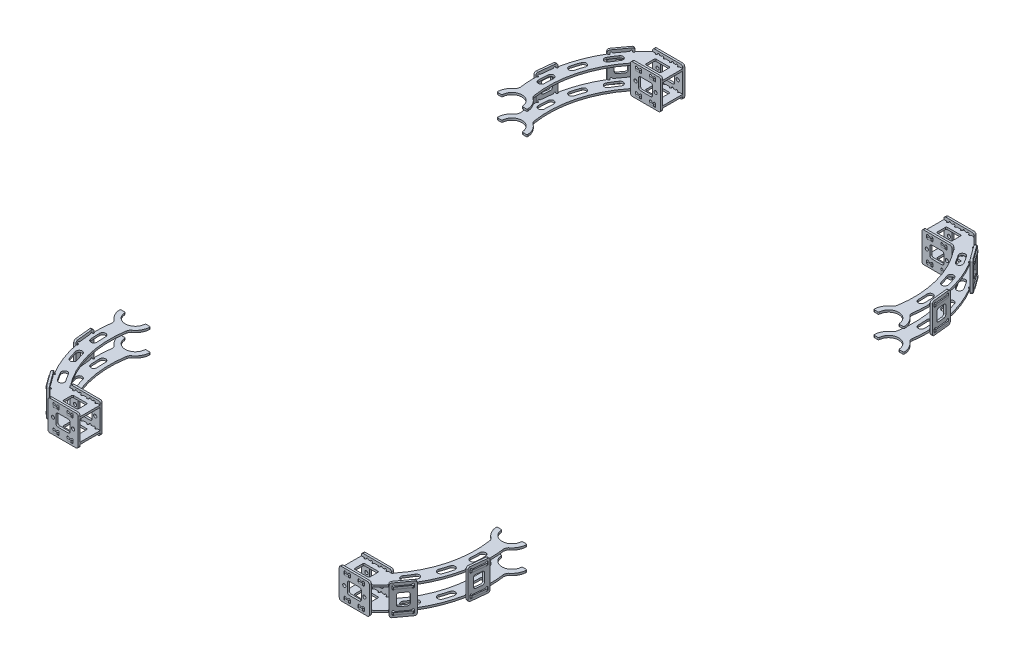
SolidWorks part; units mm, degrees
material "碳板"
ref_plane "前视基准面" through (0, 0, 0) normal (0, 0, 1) x (1, 0, 0)
ref_plane "上视基准面" through (0, 0, 0) normal (0, 1, 0) x (1, 0, 0)
ref_plane "右视基准面" through (0, 0, 0) normal (1, 0, 0) x (0, 0, -1)
sketch "草图1" plane through (0, 0, 0) normal (0, 1, 0) x (1, 0, 0)
  line L0 (-112.5, -92.5) -> (-54.5, -92.5) construction
  line L1 (-112.5, 112.5) -> (112.5, 112.5) construction
  line L2 (-112.5, 112.5) -> (-112.5, -112.5) construction
  line L3 (-112.5, -112.5) -> (112.5, -112.5) construction
  line L4 (112.5, 112.5) -> (112.5, -112.5) construction
  line L5 (-112.5, 112.5) -> (112.5, -112.5) construction
  line L6 (-112.5, -112.5) -> (112.5, 112.5) construction
  line L7 (-27.5, -92.5) -> (-27.5, -112.5) construction
  line L8 (0, 37.5843) -> (0, -27.5249) construction
  line L9 (-40.5136, 0) -> (50.3347, 0) construction
  line L10 (-27.5, -92.5) -> (-30.5, -92.5)
  line L11 (-57.5, -92.5) -> (-57.5, -112.5)
  line L12 (-57.5, -112.5) -> (-54.5, -112.5)
  line L13 (-52.5, -92.5) -> (-52.5, -89.5)
  line L14 (-52.5, -89.5) -> (-46.5, -89.5)
  line L15 (-46.5, -89.5) -> (-46.5, -92.5)
  line L16 (-54.5, -92.5) -> (-57.5, -92.5)
  line L17 (-15, 0) -> (-10, 0)
  line L18 (-38.5, -92.5) -> (-38.5, -89.5)
  line L19 (-38.5, -89.5) -> (-32.5, -89.5)
  line L20 (-32.5, -89.5) -> (-32.5, -92.5)
  line L21 (-40.5, -92.5) -> (-44.5, -92.5)
  line L22 (-50, -97.5) -> (-35, -97.5)
  line L23 (-50, -97.5) -> (-50, -107.5)
  line L24 (-44.5, -92.5) -> (-40.5, -92.5) construction
  line L25 (-50, -107.5) -> (-35, -107.5)
  line L26 (-30.5, -92.5) -> (-27.5, -92.5) construction
  line L27 (-57.5, -102.5) -> (-27.5, -102.5) construction
  line L28 (-32.5, -115.5) -> (-32.5, -112.5)
  line L29 (-38.5, -115.5) -> (-32.5, -115.5)
  line L30 (-38.5, -112.5) -> (-38.5, -115.5)
  line L31 (-46.5, -115.5) -> (-46.5, -112.5)
  line L32 (-52.5, -115.5) -> (-46.5, -115.5)
  line L33 (-52.5, -112.5) -> (-52.5, -115.5)
  line L34 (-35, -97.5) -> (-35, -107.5)
  line L35 (-44.5, -112.5) -> (-40.5, -112.5)
  line L36 (-50, -97.5) -> (-35, -107.5) construction
  line L37 (-30.5, -112.5) -> (-27.5, -112.5)
  line L38 (-102.3264, -30.8715) -> (1.0434, -105.9741) construction
  line L39 (-36.3635, -128.4747) -> (7.5532, -68.0286) construction
  line L40 (-17.7387, -102.2166) -> (-15.0153, -104.1953)
  line L41 (-15.0153, -104.1953) -> (-5.6107, -91.251)
  line L42 (-8.3342, -89.2723) -> (-5.6107, -91.251)
  line L43 (-102.3264, -30.8715) -> (24.709, -44.2235) construction
  line L44 (10.047, -21.0847) -> (5.395, -65.3452) construction
  line L45 (11.6216, -34.8039) -> (9.9491, -50.7162)
  line L46 (9.9491, -50.7162) -> (6.6012, -50.3643)
  line L47 (11.6216, -34.8039) -> (8.2737, -34.452)
  line L48 (-50, -107.5) -> (-35, -97.5) construction
  line L49 (15, 0) -> (10, 0)
  arc A0 (-10, 0) -> (10, 0) centre (0, 0) ccw
  arc A1 (-15, 0) -> (-7, -13.2665) centre (0, 0) ccw
  arc A2 (-27.5, -92.5) -> (-7, -13.2665) centre (-102.3264, -30.8715) ccw
  arc A3 (-27.5, -112.5) -> (-18.9815, -103.7812) centre (-102.3264, -30.8715) ccw
  arc A6 (7, -13.2665) -> (15, 0) centre (0, 0) ccw
  arc A7 (-54.5, -92.5) -> (-52.5, -92.5) centre (-53.5, -92.5) ccw
  arc A8 (-46.5, -92.5) -> (-44.5, -92.5) centre (-45.5, -92.5) ccw
  arc A9 (-40.5, -92.5) -> (-38.5, -92.5) centre (-39.5, -92.5) ccw
  arc A10 (-32.5, -92.5) -> (-30.5, -92.5) centre (-31.5, -92.5) ccw
  arc A11 (-32.5, -112.5) -> (-30.5, -112.5) centre (-31.5, -112.5) cw
  arc A12 (-40.5, -112.5) -> (-38.5, -112.5) centre (-39.5, -112.5) cw
  arc A13 (-46.5, -112.5) -> (-44.5, -112.5) centre (-45.5, -112.5) cw
  arc A14 (-54.5, -112.5) -> (-52.5, -112.5) centre (-53.5, -112.5) cw
  arc A15 (-7.2301, -87.6069) -> (6.3073, -52.3408) centre (-102.3264, -30.8715) ccw
  arc A16 (8.3971, -32.4577) -> (7, -13.2665) centre (-102.3264, -30.8715) ccw
  arc A17 (-17.7387, -102.2166) -> (-18.9815, -103.7812) centre (-18.3265, -103.0256) ccw
  arc A18 (-7.2301, -87.6069) -> (-8.3342, -89.2723) centre (-7.7464, -88.4633) ccw
  arc A19 (6.6012, -50.3643) -> (6.3073, -52.3408) centre (6.4967, -51.3589) ccw
  arc A20 (8.3971, -32.4577) -> (8.2737, -34.452) centre (8.3782, -33.4575) ccw
  point P0 (0, 0)
  point P22 (-13.5993, 6.3293)
  point P67 (-10.313, -97.7232)
  point P74 (10.7854, -42.76)
  point P76 (-42.5, -102.5)
  dimension "D4" = 20
  dimension "D5" = 30
  dimension "D6" = 14
  dimension "D7" = 30
  dimension "D11" = 2
  dimension "D20" = 2
  dimension "D1" = 225
  dimension "D2" = 85
  dimension "D3" = 20
  dimension "D8" = 3
  dimension "D9" = 6
  dimension "D10" = 5
  dimension "D13" = 14
  dimension "D14" = 36
  dimension "D15" = 3
  dimension "D16" = 16
  dimension "D17" = 6
  dimension "D18" = 3
  dimension "D19" = 16
  dimension "D21" = 10
  dimension "D22" = 15
  dimension "D12" = 2
extrude "凸台-拉伸1" add sketch "草图1" along normal blind 2 from offset 10
sketch "草图2" plane through (0, 12, 0) normal (0, 1, 0) x (1, 0, 0)
  line L0 (-102.3264, -30.8715) -> (46.3738, -30.8715) construction
  line L1 (-102.3264, -30.8715) -> (1.2779, -39.9357) construction
  line L2 (-102.3264, -30.8715) -> (-1.7107, -39.6743) construction
  line L3 (-102.3264, -30.8715) -> (-7.4174, -65.4156) construction
  arc A0 (-27.5, -92.5) -> (-7, -13.2665) centre (-102.3264, -30.8715) ccw construction
  arc A1 (-27.5, -92.5) -> (-7, -13.2665) centre (-102.3264, -30.8715) ccw construction
  circle A2 centre (-102.3264, -30.8715) radius 104 construction
  arc A3 (1.6736, -30.8715) -> (1.2779, -39.9357) centre (-102.3264, -30.8715) cw construction
  arc A4 (4.2664, -40.1972) -> (4.6736, -30.8715) centre (-102.3264, -30.8715) ccw
  arc A5 (-1.7107, -39.6743) -> (-1.3264, -30.8715) centre (-102.3264, -30.8715) ccw
  arc A6 (-1.7107, -39.6743) -> (4.2664, -40.1972) centre (1.2779, -39.9357) ccw
  arc A7 (4.6736, -30.8715) -> (-1.3264, -30.8715) centre (1.6736, -30.8715) ccw
  arc A8 (-7.4174, -65.4156) -> (-4.7679, -57.0122) centre (-102.3264, -30.8715) ccw
  arc A9 (-7.4174, -65.4156) -> (-1.7793, -67.4677) centre (-4.5984, -66.4416) ccw
  arc A10 (1.0277, -58.5652) -> (-4.7679, -57.0122) centre (-1.8701, -57.7887) ccw
  arc A11 (-1.7793, -67.4677) -> (1.0277, -58.5652) centre (-102.3264, -30.8715) ccw
  arc A12 (-1.8701, -57.7887) -> (-4.5984, -66.4416) centre (-102.3264, -30.8715) cw construction
  arc A13 (-19.592, -88.8027) -> (-14.8578, -81.3715) centre (-102.3264, -30.8715) ccw
  arc A14 (-19.592, -88.8027) -> (-14.6771, -92.2442) centre (-17.1346, -90.5235) ccw
  arc A15 (-9.6617, -84.3715) -> (-14.8578, -81.3715) centre (-12.2598, -82.8715) ccw
  arc A16 (-14.6771, -92.2442) -> (-9.6617, -84.3715) centre (-102.3264, -30.8715) ccw
  arc A17 (-12.2598, -82.8715) -> (-17.1346, -90.5235) centre (-102.3264, -30.8715) cw construction
  circle A18 centre (-27.5, -91.5) radius 1
  point P7 (1.5746, -35.4079)
  point P18 (-3.1398, -62.1449)
  point P25 (-14.6137, -86.7507)
  dimension "D1" = 208
  dimension "D2" = 3
  dimension "D6" = 2
  dimension "D3" = 5
  dimension "D5" = 15
  dimension "D4" = 3
extrude "切除-拉伸1" cut sketch "草图2" against normal through all
chamfer "倒角1" distance 1 angle 45 12 edges at (11.6216, 11, 34.8039) (9.9491, 11, 50.7162) (-5.6107, 11, 91.251) (-15.0153, 11, 104.1953) (-32.5, 11, 115.5) (-38.5, 11, 115.5) (-46.5, 11, 115.5) (-52.5, 11, 115.5) (-32.5, 11, 89.5) (-38.5, 11, 89.5) (-46.5, 11, 89.5) (-52.5, 11, 89.5)
fillet "圆角1" radius 5 3 edges at (-7, 11, 13.2665) (7, 11, 13.2665) (-27.5, 11, 112.5)
fillet "圆角5" radius 1 8 edges at (-50, 11, 107.5) (-35, 11, 107.5) (-35, 11, 97.5) (-50, 11, 97.5) (15, 11, 0) (10, 11, 0) (-15, 11, 0) (-10, 11, 0)
mirror "镜向1" about plane through (0, 0, 0) normal (0, 1, 0) of bodies 107
sketch "草图3" plane through (0, 0, 112.5) normal (0, 0, 1) x (1, 0, 0)
  line L0 (-42.5, 12) -> (-42.5, -12) construction
  line L1 (-44.5, 12) -> (-40.5, 12) construction
  line L2 (-44.5, -12) -> (-40.5, -12) construction
  line L3 (-51.5, 12) -> (-47.5, 12) construction
  line L4 (-51.5, 12) -> (-47.5, 12) construction
  line L5 (-51.5, 10) -> (-47.5, 10) construction
  line L6 (-51.5, 10) -> (-47.5, 10) construction
  line L7 (-49.5, 12) -> (-49.5, 10) construction
  line L9 (-50.6, 12.1) -> (-48.4, 12.1)
  line L10 (-52.6, 12.1) -> (-52.6, 9.9)
  line L11 (-50.6, 9.9) -> (-48.4, 9.9)
  line L12 (-46.4, 12.1) -> (-46.4, 9.9)
  line L13 (-52.6, 12.1) -> (-46.4, 9.9) construction
  line L14 (-52.6, 9.9) -> (-46.4, 12.1) construction
  line L15 (-32.4, 12.1) -> (-32.4, 9.9)
  line L16 (-34.4, 12.1) -> (-36.6, 12.1)
  line L17 (-38.6, 12.1) -> (-38.6, 9.9)
  line L18 (-34.4, 9.9) -> (-36.6, 9.9)
  line L19 (-81.2363, 0) -> (-40.6894, 0) construction
  line L20 (-52.6, -9.9) -> (-46.4, -12.1) construction
  line L21 (-52.6, -12.1) -> (-46.4, -9.9) construction
  line L22 (-49.5, -12) -> (-49.5, -10) construction
  line L23 (-51.5, -10) -> (-47.5, -10) construction
  line L24 (-51.5, -12) -> (-47.5, -12) construction
  line L25 (-34.4, -9.9) -> (-36.6, -9.9)
  line L26 (-38.6, -12.1) -> (-38.6, -9.9)
  line L27 (-34.4, -12.1) -> (-36.6, -12.1)
  line L28 (-32.4, -12.1) -> (-32.4, -9.9)
  line L29 (-46.4, -12.1) -> (-46.4, -9.9)
  line L30 (-50.6, -9.9) -> (-48.4, -9.9)
  line L31 (-52.6, -12.1) -> (-52.6, -9.9)
  line L32 (-50.6, -12.1) -> (-48.4, -12.1)
  line L33 (-57.5, -12) -> (-57.5, -10) construction
  line L34 (-57.5, 15) -> (-27.5, 15)
  line L35 (-57.5, 15) -> (-57.5, -15)
  line L36 (-57.5, -15) -> (-27.5, -15)
  line L37 (-27.5, 15) -> (-27.5, -15)
  line L38 (-57.5, 15) -> (-27.5, -15) construction
  line L39 (-57.5, -15) -> (-27.5, 15) construction
  line L41 (-49.5, 6) -> (-35.5, 6)
  line L42 (-49.5, 6) -> (-49.5, -6)
  line L43 (-49.5, -6) -> (-35.5, -6)
  line L44 (-35.5, 6) -> (-35.5, -6)
  line L45 (-49.5, 6) -> (-35.5, -6) construction
  line L46 (-49.5, -6) -> (-35.5, 6) construction
  arc A0 (-50.6, 12.1) -> (-52.6, 12.1) centre (-51.6, 12.1) ccw
  arc A1 (-52.6, 9.9) -> (-50.6, 9.9) centre (-51.6, 9.9) ccw
  arc A2 (-46.4, 12.1) -> (-48.4, 12.1) centre (-47.4, 12.1) ccw
  arc A3 (-48.4, 9.9) -> (-46.4, 9.9) centre (-47.4, 9.9) ccw
  arc A4 (-32.4, 9.9) -> (-34.4, 9.9) centre (-33.4, 9.9) cw
  arc A5 (-34.4, 12.1) -> (-32.4, 12.1) centre (-33.4, 12.1) cw
  arc A6 (-38.6, 12.1) -> (-36.6, 12.1) centre (-37.6, 12.1) cw
  arc A7 (-36.6, 9.9) -> (-38.6, 9.9) centre (-37.6, 9.9) cw
  arc A8 (-36.6, -9.9) -> (-38.6, -9.9) centre (-37.6, -9.9) ccw
  arc A9 (-38.6, -12.1) -> (-36.6, -12.1) centre (-37.6, -12.1) ccw
  arc A10 (-34.4, -12.1) -> (-32.4, -12.1) centre (-33.4, -12.1) ccw
  arc A11 (-32.4, -9.9) -> (-34.4, -9.9) centre (-33.4, -9.9) ccw
  arc A12 (-48.4, -9.9) -> (-46.4, -9.9) centre (-47.4, -9.9) cw
  arc A13 (-46.4, -12.1) -> (-48.4, -12.1) centre (-47.4, -12.1) cw
  arc A14 (-52.6, -9.9) -> (-50.6, -9.9) centre (-51.6, -9.9) cw
  arc A15 (-50.6, -12.1) -> (-52.6, -12.1) centre (-51.6, -12.1) cw
  circle A16 centre (-52.5, 0) radius 1.6
  circle A17 centre (-32.5, 0) radius 1.6
  point P12 (-49.5, 11)
  point P70 (-49.5, -11)
  point P71 (-42.5, 0)
  point P82 (-42.5, 0)
  dimension "D3" = 2
  dimension "D5" = 3.2
  dimension "D1" = 6.2
  dimension "D2" = 2.2
  dimension "D4" = 30
  dimension "D6" = 20
  dimension "D7" = 12
  dimension "D8" = 14
extrude "凸台-拉伸2" add sketch "草图3" along normal blind 2 separate body
fillet "圆角2" radius 2 8 edges at (-49.5, 6, 113.5) (-35.5, -6, 113.5) (-35.5, 6, 113.5) (-49.5, -6, 113.5) (-27.5, -15, 113.5) (-57.5, -15, 113.5) (-27.5, 15, 113.5) (-57.5, 15, 113.5)
ref_plane "基准面1" through (0, 0, 102.5) normal (0, 0, 1) x (1, 0, 0)
mirror "镜向2" about plane through (0, 0, 102.5) normal (0, 0, 1) of bodies 109
sketch "草图4" plane through (39.7202, 0, 28.8584) normal (0.809, 0, 0.5878) x (0.5878, 0, -0.809)
  line L0 (-85.1215, 12) -> (-85.1215, -12) construction
  line L1 (-92.1215, 12) -> (-78.1215, 12) construction
  line L2 (-92.1215, -12) -> (-78.1215, -12) construction
  line L3 (-93.4166, 0) -> (-61.3363, 0) construction
  line L4 (-92.1215, 11) -> (-78.1215, 11) construction
  line L5 (-92.1215, 12) -> (-92.1215, 10) construction
  line L6 (-78.1215, 10) -> (-78.1215, 12) construction
  line L7 (-93.2215, -12.1) -> (-93.2215, -9.9)
  line L8 (-91.2215, 12.1) -> (-79.0215, 12.1)
  line L9 (-93.2215, 12.1) -> (-93.2215, 9.9)
  line L10 (-91.2215, 9.9) -> (-79.0215, 9.9)
  line L11 (-77.0215, 12.1) -> (-77.0215, 9.9)
  line L12 (-93.2215, 12.1) -> (-77.0215, 9.9) construction
  line L13 (-93.2215, 9.9) -> (-77.0215, 12.1) construction
  line L14 (-91.2215, -12.1) -> (-79.0215, -12.1)
  line L15 (-77.0215, -12.1) -> (-77.0215, -9.9)
  line L16 (-91.2215, -9.9) -> (-79.0215, -9.9)
  line L18 (-95.1215, 15) -> (-75.1215, 15)
  line L19 (-95.1215, 15) -> (-95.1215, -15)
  line L20 (-95.1215, -15) -> (-75.1215, -15)
  line L21 (-75.1215, 15) -> (-75.1215, -15)
  line L22 (-95.1215, 15) -> (-75.1215, -15) construction
  line L23 (-95.1215, -15) -> (-75.1215, 15) construction
  line L24 (-90.1215, 6) -> (-80.1215, 6)
  line L25 (-90.1215, 6) -> (-90.1215, -6)
  line L26 (-90.1215, -6) -> (-80.1215, -6)
  line L27 (-80.1215, 6) -> (-80.1215, -6)
  line L28 (-90.1215, 6) -> (-80.1215, -6) construction
  line L29 (-90.1215, -6) -> (-80.1215, 6) construction
  arc A0 (-91.2215, 12.1) -> (-93.2215, 12.1) centre (-92.2215, 12.1) ccw
  arc A1 (-93.2215, 9.9) -> (-91.2215, 9.9) centre (-92.2215, 9.9) ccw
  arc A2 (-77.0215, 12.1) -> (-79.0215, 12.1) centre (-78.0215, 12.1) ccw
  arc A3 (-79.0215, 9.9) -> (-77.0215, 9.9) centre (-78.0215, 9.9) ccw
  arc A4 (-93.2215, -9.9) -> (-91.2215, -9.9) centre (-92.2215, -9.9) cw
  arc A5 (-91.2215, -12.1) -> (-93.2215, -12.1) centre (-92.2215, -12.1) cw
  arc A6 (-77.0215, -12.1) -> (-79.0215, -12.1) centre (-78.0215, -12.1) cw
  arc A7 (-79.0215, -9.9) -> (-77.0215, -9.9) centre (-78.0215, -9.9) cw
  point P15 (-85.1215, 11)
  point P21 (-85.1215, 0)
  point P42 (-85.1215, 0)
  dimension "D3" = 2
  dimension "D1" = 2.2
  dimension "D2" = 16.2
  dimension "D4" = 20
  dimension "D5" = 30
  dimension "D6" = 10
  dimension "D7" = 12
extrude "凸台-拉伸3" add sketch "草图4" against normal blind 2 from offset 1 separate body offset against normal yes
fillet "圆角3" radius 2 8 edges at (-6.0532, 15, 88.4574) (-17.8089, -15, 104.6378) (-6.0532, -15, 88.4574) (-17.8089, 15, 104.6378) (-14.87, -6, 100.5927) (-8.9921, 6, 92.5025) (-8.9921, -6, 92.5025) (-14.87, 6, 100.5927)
sketch "草图5" plane through (15.1127, 0, 1.5884) normal (0.9945, 0, 0.1045) x (0.1045, 0, -0.9945)
  line L0 (-52.44, 0) -> (7.8582, 0) construction
  line L1 (-41.3984, 12) -> (-41.3984, -12) construction
  line L2 (-48.3984, 12) -> (-34.3984, 12) construction
  line L3 (-48.3984, -12) -> (-34.3984, -12) construction
  line L4 (-48.3984, 11) -> (-34.3984, 11) construction
  line L5 (-48.3984, 12) -> (-48.3984, 10) construction
  line L6 (-34.3984, 10) -> (-34.3984, 12) construction
  line L8 (-47.4984, 12.1) -> (-35.2984, 12.1)
  line L9 (-49.4984, 12.1) -> (-49.4984, 9.9)
  line L10 (-47.4984, 9.9) -> (-35.2984, 9.9)
  line L11 (-33.2984, 12.1) -> (-33.2984, 9.9)
  line L12 (-49.4984, 12.1) -> (-33.2984, 9.9) construction
  line L13 (-49.4984, 9.9) -> (-33.2984, 12.1) construction
  line L14 (-49.4984, -12.1) -> (-49.4984, -9.9)
  line L15 (-47.4984, -12.1) -> (-35.2984, -12.1)
  line L16 (-33.2984, -12.1) -> (-33.2984, -9.9)
  line L17 (-47.4984, -9.9) -> (-35.2984, -9.9)
  line L19 (-51.3984, 15) -> (-31.3984, 15)
  line L20 (-51.3984, 15) -> (-51.3984, -15)
  line L21 (-51.3984, -15) -> (-31.3984, -15)
  line L22 (-31.3984, 15) -> (-31.3984, -15)
  line L23 (-51.3984, 15) -> (-31.3984, -15) construction
  line L24 (-51.3984, -15) -> (-31.3984, 15) construction
  line L25 (-46.3984, 6) -> (-36.3984, 6)
  line L26 (-46.3984, 6) -> (-46.3984, -6)
  line L27 (-46.3984, -6) -> (-36.3984, -6)
  line L28 (-36.3984, 6) -> (-36.3984, -6)
  line L29 (-46.3984, 6) -> (-36.3984, -6) construction
  line L30 (-46.3984, -6) -> (-36.3984, 6) construction
  arc A0 (-47.4984, 12.1) -> (-49.4984, 12.1) centre (-48.4984, 12.1) ccw
  arc A1 (-49.4984, 9.9) -> (-47.4984, 9.9) centre (-48.4984, 9.9) ccw
  arc A2 (-33.2984, 12.1) -> (-35.2984, 12.1) centre (-34.2984, 12.1) ccw
  arc A3 (-35.2984, 9.9) -> (-33.2984, 9.9) centre (-34.2984, 9.9) ccw
  arc A4 (-49.4984, -9.9) -> (-47.4984, -9.9) centre (-48.4984, -9.9) cw
  arc A5 (-47.4984, -12.1) -> (-49.4984, -12.1) centre (-48.4984, -12.1) cw
  arc A6 (-33.2984, -12.1) -> (-35.2984, -12.1) centre (-34.2984, -12.1) cw
  arc A7 (-35.2984, -9.9) -> (-33.2984, -9.9) centre (-34.2984, -9.9) cw
  point P15 (-41.3984, 11)
  point P29 (-41.3984, 0)
  point P45 (-41.3984, 0)
  dimension "D3" = 2
  dimension "D1" = 16.2
  dimension "D2" = 2.2
  dimension "D4" = 30
  dimension "D5" = 20
  dimension "D6" = 12
  dimension "D7" = 10
extrude "凸台-拉伸4" add sketch "草图5" against normal blind 2 from offset 1 separate body offset against normal yes
fillet "圆角4" radius 2 8 edges at (7.751, 15, 52.4962) (7.751, -15, 52.4962) (9.8416, -15, 32.6058) (9.8416, 15, 32.6058) (8.2737, -6, 47.5236) (9.319, 6, 37.5784) (9.319, -6, 37.5784) (8.2737, 6, 47.5236)
ref_plane "基准面2" through (-187.5, 0, 0) normal (-1, 0, 0) x (0, 0, 1)
mirror "镜向3" about plane through (-187.5, 0, 0) normal (-1, 0, 0) of bodies 107 108 109 110 111 112
ref_plane "基准面3" through (0, 0, -187.5) normal (0, 0, -1) x (-1, 0, 0)
mirror "镜向4" about plane through (0, 0, -187.5) normal (0, 0, -1) of bodies 115 118 111 110 114 113 116 108 107 117 109 112
